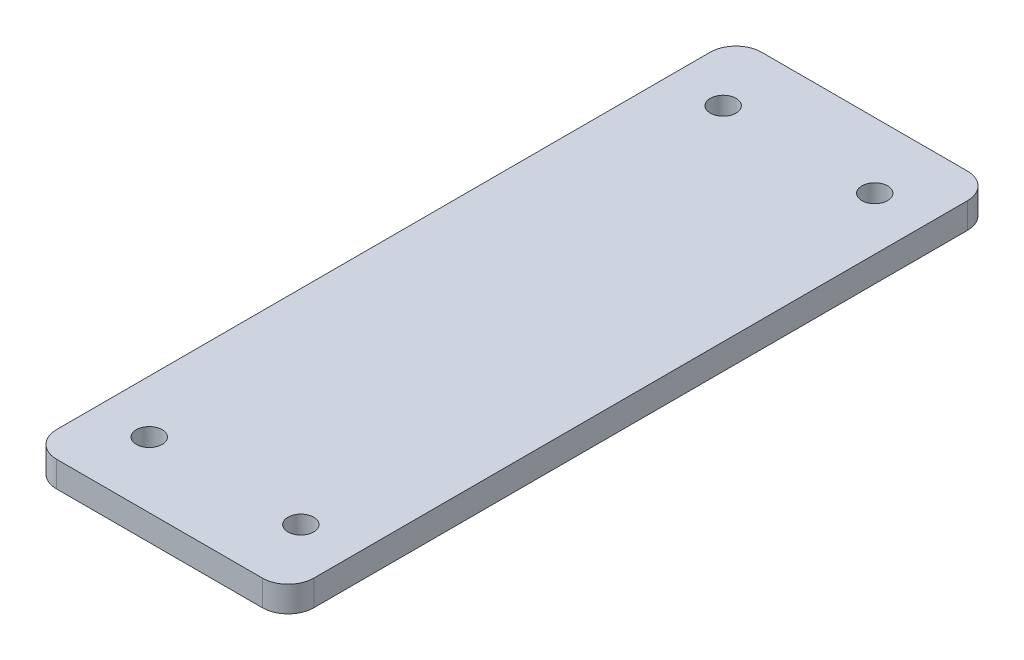
SolidWorks part; units mm, degrees
ref_plane "Front Plane" through (0, 0, 0) normal (0, 0, 1) x (1, 0, 0)
ref_plane "Top Plane" through (0, 0, 0) normal (0, 1, 0) x (1, 0, 0)
ref_plane "Right Plane" through (0, 0, 0) normal (1, 0, 0) x (0, 0, -1)
sketch "Sketch1" plane through (0, 0, 0) normal (0, 1, 0) x (1, 0, 0)
  line L0 (0, 33.4628) -> (0, -42.1291) construction
  line L1 (-39.1744, 0) -> (52.4466, 0) construction
  line L2 (-23.1, -23.1) -> (23.1, -23.1) construction
  line L3 (23.1, -23.1) -> (23.1, 23.1) construction
  line L4 (23.1, 23.1) -> (-23.1, 23.1) construction
  line L5 (-23.1, 23.1) -> (-23.1, -23.1) construction
  line L6 (-23.1, -23.1) -> (23.1, 23.1) construction
  line L7 (-23.1, 23.1) -> (23.1, -23.1) construction
  line L9 (6.5, -42.6342) -> (-6.5, -42.6342) construction
  line L10 (6.5, -42.6342) -> (6.5, 42.6342) construction
  line L11 (6.5, 42.6342) -> (-6.5, 42.6342) construction
  line L12 (-6.5, -42.6342) -> (-6.5, 42.6342) construction
  line L13 (6.5, -42.6342) -> (-6.5, 42.6342) construction
  line L14 (6.5, 42.6342) -> (-6.5, -42.6342) construction
  line L15 (-15, -41.108) -> (15, -41.108) construction
  line L16 (-15, -41.108) -> (-15, 41.108) construction
  line L17 (-15, 41.108) -> (15, 41.108) construction
  line L18 (15, -41.108) -> (15, 41.108) construction
  line L19 (-15, -41.108) -> (15, 41.108) construction
  line L20 (-15, 41.108) -> (15, -41.108) construction
  line L21 (-15, 41.108) -> (15, 41.108) construction
  line L22 (15, 41.108) -> (15, 21.6935) construction
  line L23 (-15, -21.6935) -> (-15, -41.108) construction
  line L24 (-15, -41.108) -> (15, -41.108) construction
  line L25 (15, -41.108) -> (15, -21.6935) construction
  line L27 (-12, -41.108) -> (12, -41.108)
  line L28 (-15, -38.108) -> (-15, 38.108)
  line L29 (-12, 41.108) -> (12, 41.108)
  line L30 (15, -38.108) -> (15, 38.108)
  line L31 (-15, -41.108) -> (15, 41.108) construction
  line L32 (-15, 41.108) -> (15, -41.108) construction
  circle A0 centre (0, 0) radius 23.1 construction
  circle A1 centre (0, 0) radius 9.5 construction
  circle A2 centre (0, 0) radius 12.5 construction
  circle A3 centre (-8.8388, 8.8388) radius 1.5 construction
  circle A4 centre (8.8388, -8.8388) radius 1.5 construction
  circle A5 centre (6.7175, 6.7175) radius 1.5 construction
  circle A6 centre (-6.7175, -6.7175) radius 1.5 construction
  circle A7 centre (0, 0) radius 5 construction
  arc A8 (-17.4471, 15.1396) -> (-17.4471, -15.1396) centre (0, 0) ccw construction
  arc A9 (17.4471, 15.1396) -> (17.4471, -15.1396) centre (0, 0) cw construction
  arc A10 (15, 21.6935) -> (17.4471, 15.1396) centre (25, 21.6935) ccw construction
  arc A11 (-17.4471, 15.1396) -> (-15, 21.6935) centre (-25, 21.6935) ccw construction
  arc A12 (-15, -21.6935) -> (-17.4471, -15.1396) centre (-25, -21.6935) ccw construction
  arc A13 (15, -21.6935) -> (17.4471, -15.1396) centre (25, -21.6935) cw construction
  circle A14 centre (-8.8388, 33.4628) radius 1.5 construction
  circle A15 centre (8.8388, 33.4628) radius 1.5 construction
  circle A16 centre (8.8388, -33.4628) radius 1.5 construction
  circle A17 centre (-8.8388, -33.4628) radius 1.5 construction
  circle A18 centre (-8.8388, 33.4628) radius 1.5
  circle A19 centre (8.8388, 33.4628) radius 1.5
  circle A20 centre (8.8388, -33.4628) radius 1.5
  circle A21 centre (-8.8388, -33.4628) radius 1.5
  arc A22 (15, -38.108) -> (12, -41.108) centre (12, -38.108) cw
  arc A23 (-12, -41.108) -> (-15, -38.108) centre (-12, -38.108) cw
  arc A24 (15, 38.108) -> (12, 41.108) centre (12, 38.108) ccw
  arc A25 (-12, 41.108) -> (-15, 38.108) centre (-12, 38.108) ccw
  point P38 (15, 17.5673)
  point P41 (-15, 17.5673)
  dimension "D1" = 46.2
  dimension "D3" = 10
  dimension "D4" = 10
  dimension "D5" = 10
  dimension "D6" = 10
  dimension "D7" = 3
  dimension "D2" = 13
extrude "Boss-Extrude1" add sketch "Sketch1" along normal blind 3
